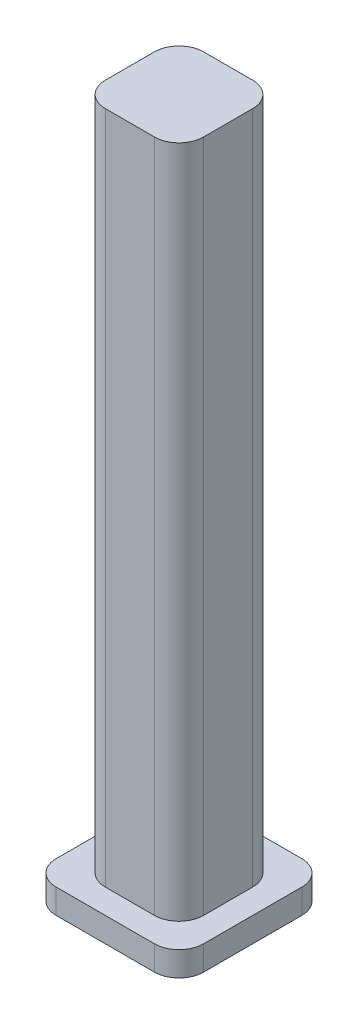
SolidWorks part; units mm, degrees
ref_plane "Front Plane" through (0, 0, 0) normal (0, 0, 1) x (1, 0, 0)
ref_plane "Top Plane" through (0, 0, 0) normal (0, 1, 0) x (1, 0, 0)
ref_plane "Right Plane" through (0, 0, 0) normal (1, 0, 0) x (0, 0, -1)
sketch "Sketch1" plane through (0, 0, 0) normal (0, 1, 0) x (1, 0, 0)
  line L1 (-30, -30) -> (30, -30)
  line L2 (-30, -30) -> (-30, 30)
  line L3 (-30, 30) -> (30, 30)
  line L4 (30, -30) -> (30, 30)
  line L5 (-30, -30) -> (30, 30) construction
  line L6 (-30, 30) -> (30, -30) construction
  point P0 (0, 0)
  dimension "D1" = 60
extrude "Boss-Extrude1" add sketch "Sketch1" along normal blind 10
sketch "Sketch2" plane through (0, 0, 0) normal (0, 1, 0) x (1, 0, 0)
  line L1 (-20, -20) -> (20, -20)
  line L2 (-20, -20) -> (-20, 20)
  line L3 (-20, 20) -> (20, 20)
  line L4 (20, -20) -> (20, 20)
  line L5 (-20, -20) -> (20, 20) construction
  line L6 (-20, 20) -> (20, -20) construction
  point P0 (0, 0)
  dimension "D1" = 40
extrude "Boss-Extrude2" add sketch "Sketch2" along normal blind 284.3555
fillet "Fillet1" radius 10 8 edges at (30, 5, -30) (-30, 5, -30) (-30, 5, 30) (30, 5, 30) (20, 147.1777, -20) (20, 147.1777, 20) (-20, 147.1777, -20) (-20, 147.1777, 20)
